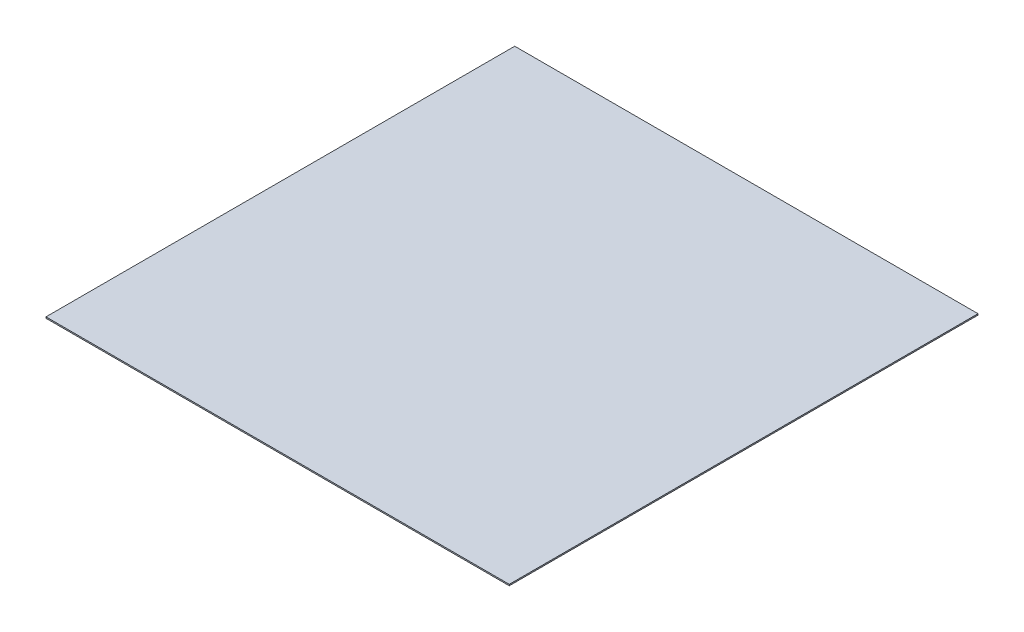
SolidWorks part; units mm, degrees
ref_plane "Front Plane" through (0, 0, 0) normal (0, 0, 1) x (1, 0, 0)
ref_plane "Top Plane" through (0, 0, 0) normal (0, 1, 0) x (1, 0, 0)
ref_plane "Right Plane" through (0, 0, 0) normal (1, 0, 0) x (0, 0, -1)
sketch "Sketch1" plane through (0, 0, 0) normal (0, 1, 0) x (1, 0, 0)
  line L1 (-895, 905.55) -> (895, 905.55)
  line L2 (-895, 905.55) -> (-895, -905.55)
  line L3 (-895, -905.55) -> (895, -905.55)
  line L4 (895, 905.55) -> (895, -905.55)
  line L5 (-895, 905.55) -> (895, -905.55) construction
  line L6 (-895, -905.55) -> (895, 905.55) construction
  point P0 (0, 0)
  dimension "D1" = 1790
  dimension "D2" = 1811.1
extrude "Boss-Extrude1" add sketch "Sketch1" along normal blind 5
